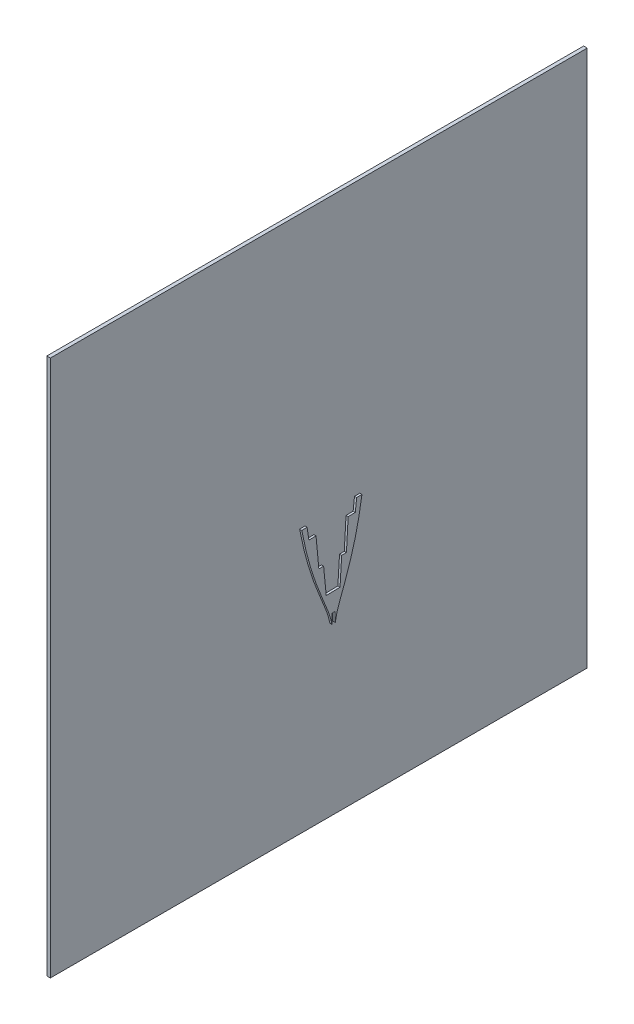
SolidWorks part; units mm, degrees
ref_plane "Plan de face" through (0, 0, 0) normal (0, 0, 1) x (1, 0, 0)
ref_plane "Plan de dessus" through (0, 0, 0) normal (0, 1, 0) x (1, 0, 0)
ref_plane "Plan de droite" through (0, 0, 0) normal (1, 0, 0) x (0, 0, -1)
sketch "Esquisse1" plane through (0, 0, 0) normal (0, 0, 1) x (1, 0, 0)
  point P0 (-20, 0)
  dimension "D1" = 20
sketch3d "Esquisse3D1"
  line L1 (-20, 1121.2893, 777.275) -> (-20, 1121.2893, -722.725)
  line L2 (-20, 1121.2893, 777.275) -> (-20, -378.7107, 777.275)
  line L3 (-20, -378.7107, 777.275) -> (-20, -378.7107, -722.725)
  line L4 (-20, 1121.2893, -722.725) -> (-20, -378.7107, -722.725)
  dimension "D1" = 1500
  dimension "D2" = 1500
extrude "Boss.-Extru.2" add sketch "Esquisse3D1" along direction (1, 0, 0) on the side of the normal blind 10 contours L2 L1 L4 L3
sketch "Esquisse4" plane through (-10, 0, 0) normal (1, 0, 0) x (0, 0, -1)
  line L0 (0, 0) -> (-7.701, 425.1082) construction
  line L1 (169.3944, 339.9131) -> (-188.5193, 333.4294) construction
  line L2 (-187.2006, 249.23) -> (169.0622, 255.6839) construction
  line L3 (-144.268, 175.2448) -> (126.4811, 180.1495) construction
sketch "Esquisse5" plane through (0, 0, 0) normal (1, 0, 0) x (0, 0, -1)
  line L0 (-7.701, 425.1082) -> (0, 0) construction
  line L2 (0, 0) -> (-2.2319, 123.2058) construction
  line L3 (-2.2319, 123.2058) -> (-2.2466, 124.0146) construction
  line L4 (-2.2466, 124.0146) -> (50.2351, 188.4283) construction
  line L5 (50.2351, 188.4283) -> (77.2873, 372.1228) construction
  line L7 (0, 0) -> (-7.701, 425.1082) construction
  line L8 (77.2873, 372.1228) -> (62.5152, 371.8552)
  line L9 (62.5152, 371.8552) -> (58.7036, 337.9079)
  line L10 (169.3944, 339.9131) -> (-188.5193, 333.4294) construction
  line L11 (58.7036, 337.9079) -> (38.7922, 337.5472)
  line L12 (38.7922, 337.5472) -> (33.9554, 253.2364)
  line L13 (-187.2006, 249.23) -> (169.0622, 255.6839) construction
  line L14 (33.9554, 253.2364) -> (20.6571, 252.9955)
  line L15 (20.6571, 252.9955) -> (16.0435, 178.1489)
  line L16 (-144.268, 175.2448) -> (126.4811, 180.1495) construction
  line L17 (16.0435, 178.1489) -> (-22.4853, 177.4509)
  line L18 (0, 0) -> (-2.2319, 123.2058) construction
  line L19 (-2.2319, 123.2058) -> (-2.2466, 124.0146) construction
  line L20 (-2.2466, 124.0146) -> (-57.0268, 186.4852) construction
  line L21 (-57.0268, 186.4852) -> (-90.7145, 369.0794) construction
  line L22 (-29.8068, 252.0813) -> (-22.4853, 177.4509)
  line L23 (-43.1051, 251.8404) -> (-29.8068, 252.0813)
  line L24 (-50.9923, 335.9207) -> (-43.1051, 251.8404)
  line L25 (-70.9037, 335.56) -> (-50.9923, 335.9207)
  line L26 (-75.9423, 369.347) -> (-70.9037, 335.56)
  line L27 (-90.7145, 369.0794) -> (-75.9423, 369.347)
  spline S0 degree 4 poles (0, 0) (-2.2319, 123.2058) (-2.2466, 124.0146) (50.2351, 188.4283) (77.2873, 372.1228) knots 0 0 0 0 0 1 1 1 1 1
  spline S1 degree 4 poles (0, 0) (-2.2319, 123.2058) (-2.2466, 124.0146) (-57.0268, 186.4852) (-90.7145, 369.0794) knots 0 0 0 0 0 1 1 1 1 1
  point P30 (-3.2209, 177.7999)
extrude "Boss.-Extru.3" add sketch "Esquisse5" along normal blind 6 separate body
sketch "Esquisse6" plane through (6, 0, 0) normal (1, 0, 0) x (0, 0, -1)
  line L0 (-6.3006, 99.3172) -> (-6.7898, 126.3172)
  line L1 (-6.7898, 126.3172) -> (2.2102, 126.4802)
  line L2 (2.2102, 126.4802) -> (2.6994, 99.4802)
  line L3 (2.6994, 99.4802) -> (117.0633, -47.527)
  line L4 (117.0633, -47.527) -> (-85.2277, -65.22)
  line L5 (-85.2277, -65.22) -> (-6.3006, 99.3172)
  line L6 (-6.3006, 99.3172) -> (2.6994, 99.4802) construction
  line L7 (-144.268, 175.2448) -> (126.4811, 180.1495) construction
  spline S0 degree 4 poles (-90.7145, 369.0794) (-57.0268, 186.4852) (-2.2466, 124.0146) (-2.2319, 123.2058) (0, 0) knots 0 0 0 0 0 1 1 1 1 1 construction
  spline S1 degree 4 poles (0, 0) (-2.2319, 123.2058) (-2.2466, 124.0146) (50.2351, 188.4283) (77.2873, 372.1228) knots 0 0 0 0 0 1 1 1 1 1 construction
  dimension "D1" = 9
  dimension "D2" = 27
extrude "Enlèv. mat.-Extru.1" cut sketch "Esquisse6" against normal blind 6
